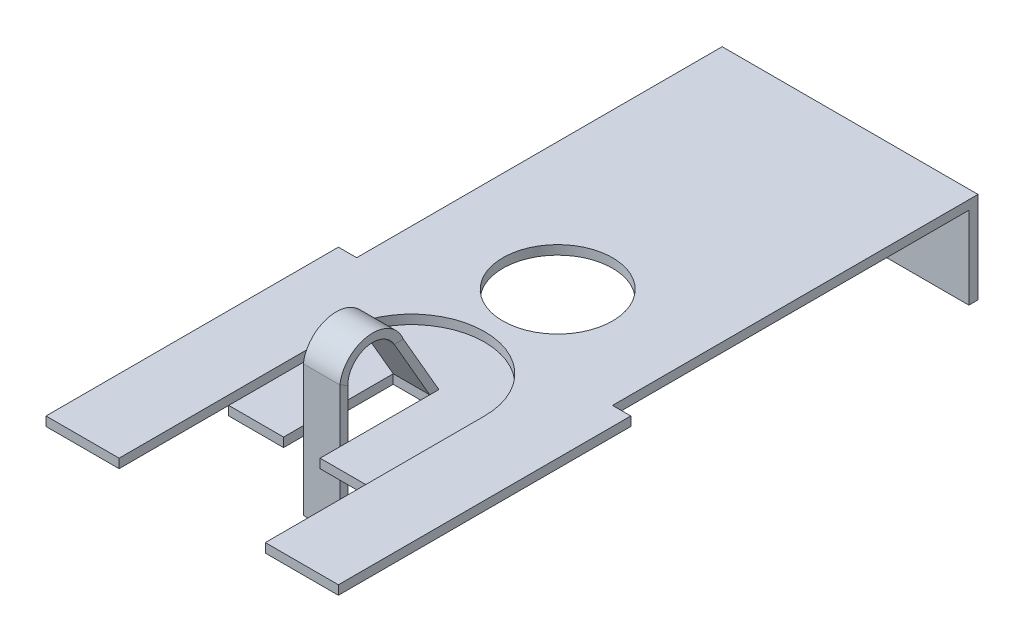
SolidWorks part; units mm, degrees
ref_plane "Front Plane" through (0, 0, 0) normal (0, 0, 1) x (1, 0, 0)
ref_plane "Top Plane" through (0, 0, 0) normal (0, 1, 0) x (1, 0, 0)
ref_plane "Right Plane" through (0, 0, 0) normal (1, 0, 0) x (0, 0, -1)
sketch "Sketch1" plane through (0, 0, 0) normal (0, 1, 0) x (1, 0, 0)
  line L0 (0, 0) -> (0, 30.6224) construction
  line L1 (-6.35, -6.35) -> (-3.175, -6.35)
  line L2 (-6.35, -6.35) -> (-6.35, 6.35)
  line L3 (-6.35, 6.35) -> (-5.5563, 6.35)
  line L4 (6.35, -6.35) -> (6.35, 6.35)
  line L5 (-6.35, -6.35) -> (6.35, 6.35) construction
  line L6 (-6.35, 6.35) -> (6.35, -6.35) construction
  line L7 (0, 0) -> (0, -13.2108) construction
  line L8 (5.5562, 22.225) -> (-5.5563, 22.225)
  line L9 (5.5562, 22.225) -> (5.5562, 6.35)
  line L11 (-5.5563, 22.225) -> (-5.5563, 6.35)
  line L12 (5.5562, 22.225) -> (-5.5563, 6.35) construction
  line L13 (5.5562, 6.35) -> (-5.5563, 22.225) construction
  line L14 (3.175, -6.35) -> (6.35, -6.35)
  line L16 (3.175, 0) -> (3.175, -6.35)
  line L18 (-3.175, 0) -> (-3.175, -6.35)
  line L19 (3.175, 0) -> (-3.175, -6.35) construction
  line L20 (3.175, -6.35) -> (-3.175, 0) construction
  line L21 (5.5562, 6.35) -> (6.35, 6.35)
  line L24 (-3.175, 0) -> (-3.175, 3.175)
  line L26 (3.175, 0) -> (3.175, 3.175)
  circle A0 centre (0, 9.525) radius 2.3813
  arc A1 (-3.175, 3.175) -> (3.175, 3.175) centre (0, 3.175) cw
  point P0 (0, 0)
  point P8 (0, 14.2875)
  point P16 (0, -3.175)
  point P24 (0, 6.35)
  dimension "D6" = 4.7625
  dimension "D1" = 12.7
  dimension "D2" = 12.7
  dimension "D3" = 0.7937
  dimension "D4" = 15.875
  dimension "D5" = 12.7
  dimension "D7" = 6.35
  dimension "D8" = 6.35
  dimension "D9" = 3.175
extrude "Boss-Extrude1" add sketch "Sketch1" along normal blind 0.3969
sketch "Sketch3" plane through (0, 0, 0) normal (0, -1, 0) x (1, 0, 0)
  line L0 (3.175, -3.175) -> (3.175, 6.35) construction
  line L2 (-3.175, -3.175) -> (-3.175, 1.5875)
  line L3 (-3.175, 1.5875) -> (-0.7937, 1.5875)
  line L4 (3.175, -3.175) -> (3.175, 1.5875)
  line L5 (-3.175, 6.35) -> (-3.175, -3.175) construction
  line L6 (0, 0) -> (0, -3.3118) construction
  line L8 (0.7937, 1.5875) -> (0.7938, -3.175)
  line L9 (0.7938, -3.175) -> (-0.7937, -3.175)
  line L10 (-0.7937, 1.5875) -> (-0.7937, -3.175)
  line L11 (0.7937, 1.5875) -> (3.175, 1.5875)
  arc A0 (3.175, -3.175) -> (-3.175, -3.175) centre (0, -3.175) cw
  arc A1 (-3.175, -3.175) -> (3.175, -3.175) centre (0, -3.175) ccw construction
  point P9 (0, -6.35)
  point P16 (0, -6.35)
  dimension "D1" = 7.9375
  dimension "D2" = 4.7625
  dimension "D3" = 1.5875
extrude "Boss-Extrude3" add sketch "Sketch3" along normal blind 0.3969 separate body
sketch "Sketch5" plane through (0, 0, 0) normal (1, 0, 0) x (0, 0, -1)
  line L0 (3.175, 0) -> (1.6331, 2.6707)
  line L1 (3.175, 0) -> (-1.5875, 0) construction
  line L2 (-0.3868, 2.1294) -> (-0.3868, -3.5719)
  line L3 (3.175, -0.3969) -> (-1.5875, -0.3969) construction
  line L4 (-1.5875, -0.3969) -> (-1.5875, 0) construction
  arc A0 (1.6331, 2.6707) -> (-0.3868, 2.1294) centre (0.6957, 2.1294) ccw
  point P6 (-0.3868, 2.475)
  point P13 (-1.5875, -0.1984)
  point P14 (-0.3868, 2.8782)
  point P15 (0.4155, 3.175)
  dimension "D1" = 3.175
  dimension "D2" = 60
  dimension "D3" = 3.175
  dimension "D4" = 1.2007
  dimension "D5" = 3.175
sketch "Sketch6" plane through (0, 0, 0) normal (0, 1, 0) x (1, 0, 0)
  line L0 (0.7937, -1.5875) -> (0.7938, 3.175) construction
  line L1 (-0.7937, 3.175) -> (0.7937, 3.175)
  line L2 (-0.7937, 3.175) -> (-0.7937, 3.5719)
  line L3 (-0.7937, 3.5719) -> (0.7937, 3.5719)
  line L4 (0.7937, 3.175) -> (0.7937, 3.5719)
  dimension "D1" = 0.3969
sweep "Sweep1" add profiles "Sketch6" path "Sketch5"
sketch "Sketch7" plane through (0, 0, -22.225) normal (0, 0, -1) x (-1, 0, 0)
  line L0 (0.7937, -3.5719) -> (-0.7937, -3.5719) construction
  line L1 (-5.5562, 0) -> (5.5563, 0)
  line L2 (-5.5562, 0) -> (-5.5562, -3.5719)
  line L3 (-5.5562, -3.5719) -> (5.5563, -3.5719)
  line L4 (5.5563, 0) -> (5.5563, -3.5719)
  line L5 (5.5563, 0.3969) -> (5.5563, 0) construction
extrude "Boss-Extrude4" add sketch "Sketch7" against normal blind 0.3969
